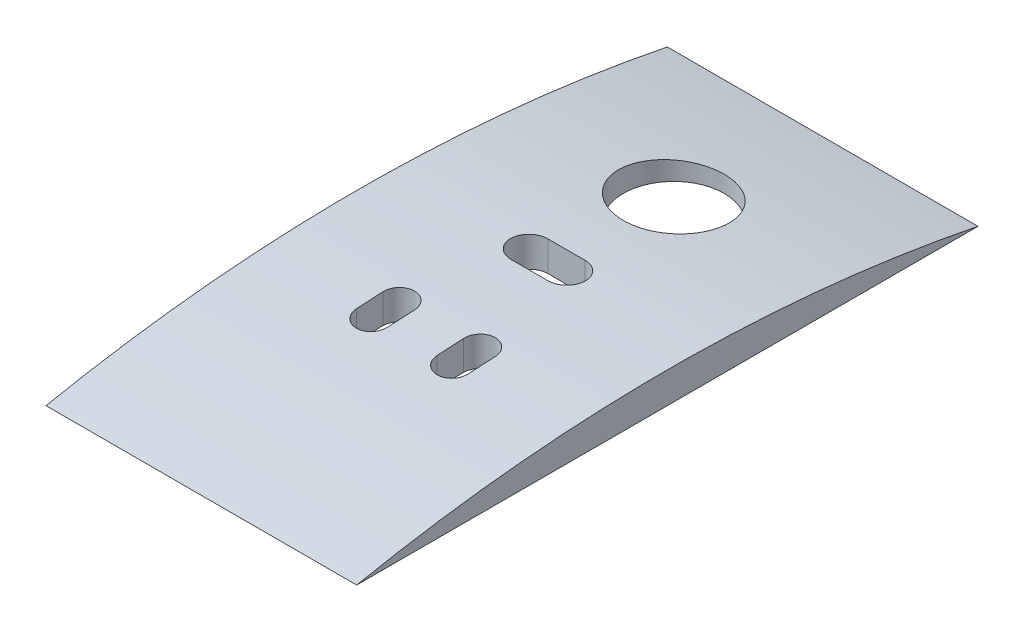
SolidWorks part; units mm, degrees
ref_plane "Front Plane" through (0, 0, 0) normal (0, 0, 1) x (1, 0, 0)
ref_plane "Top Plane" through (0, 0, 0) normal (0, 1, 0) x (1, 0, 0)
ref_plane "Right Plane" through (0, 0, 0) normal (1, 0, 0) x (0, 0, -1)
sketch "Sketch1" plane through (0, 0, 0) normal (0, 1, 0) x (1, 0, 0)
  line L1 (0, 0) -> (50.8, 0)
  line L2 (0, 0) -> (0, 101.6)
  line L3 (0, 101.6) -> (50.8, 101.6)
  line L4 (50.8, 0) -> (50.8, 101.6)
extrude "Boss-Extrude1" add sketch "Sketch1" along normal blind 76.962
sketch "Sketch2" plane through (50.8, 0, 0) normal (1, 0, 0) x (0, 0, -1)
  line L0 (50.8, 5.08) -> (50.8, 0)
  line L2 (0, 0) -> (101.6, 0) construction
  line L3 (0, 0) -> (101.6, 0)
  arc A0 (0, 0) -> (101.6, 0) centre (50.8, -251.46) cw
  line M3 (101.6, 0) -> (101.6, 76.962)
  line M4 (101.6, 76.962) -> (0, 76.962)
  line M5 (0, 76.962) -> (0, 0)
extrude "Cut-Extrude1" cut sketch "Sketch2" against normal through all contours A0 M5 M3 M4
sketch "Sketch5" plane through (0, 0, 0) normal (0, -1, 0) x (1, 0, 0)
  line L0 (0, -101.6) -> (22.3548, -56.7043) construction
  line L1 (18.7988, -34.5386) -> (18.7988, -38.8753) construction
  line L2 (21.3777, -34.5386) -> (21.3777, -38.8753)
  line L3 (16.2198, -34.5386) -> (16.2198, -38.8753)
  line L4 (32.0041, -34.5386) -> (32.0041, -38.8753) construction
  line L5 (34.583, -34.5386) -> (34.583, -38.8753)
  line L6 (29.4251, -34.5386) -> (29.4251, -38.8753)
  line L10 (22.3548, -56.7043) -> (28.4078, -56.7043) construction
  line L13 (22.3548, -53.6697) -> (28.4078, -53.6697)
  line L14 (22.3548, -59.739) -> (28.4078, -59.739)
  arc A6 (21.3777, -34.5386) -> (16.2198, -34.5386) centre (18.7988, -34.5386) ccw
  arc A7 (16.2198, -38.8753) -> (21.3777, -38.8753) centre (18.7988, -38.8753) ccw
  arc A8 (34.583, -34.5386) -> (29.4251, -34.5386) centre (32.0041, -34.5386) ccw
  arc A9 (29.4251, -38.8753) -> (34.583, -38.8753) centre (32.0041, -38.8753) ccw
  arc A14 (22.3548, -53.6697) -> (22.3548, -59.739) centre (22.3548, -56.7043) ccw
  arc A15 (28.4078, -59.739) -> (28.4078, -53.6697) centre (28.4078, -56.7043) ccw
  point P13 (18.7988, -36.7069)
  point P21 (32.0041, -36.7069)
  point P26 (25.3813, -56.7043)
sketch "Sketch6" plane through (0, 0, 0) normal (0, -1, 0) x (1, 0, 0)
  line L2 (0, -101.6) -> (19.4409, -82.9632)
  circle A0 centre (25.4, -77.2506) radius 8.255
extrude "Cut-Extrude2" cut sketch "Sketch6" against normal through all contours A0
extrude "Cut-Extrude3" cut sketch "Sketch5" against normal through all
